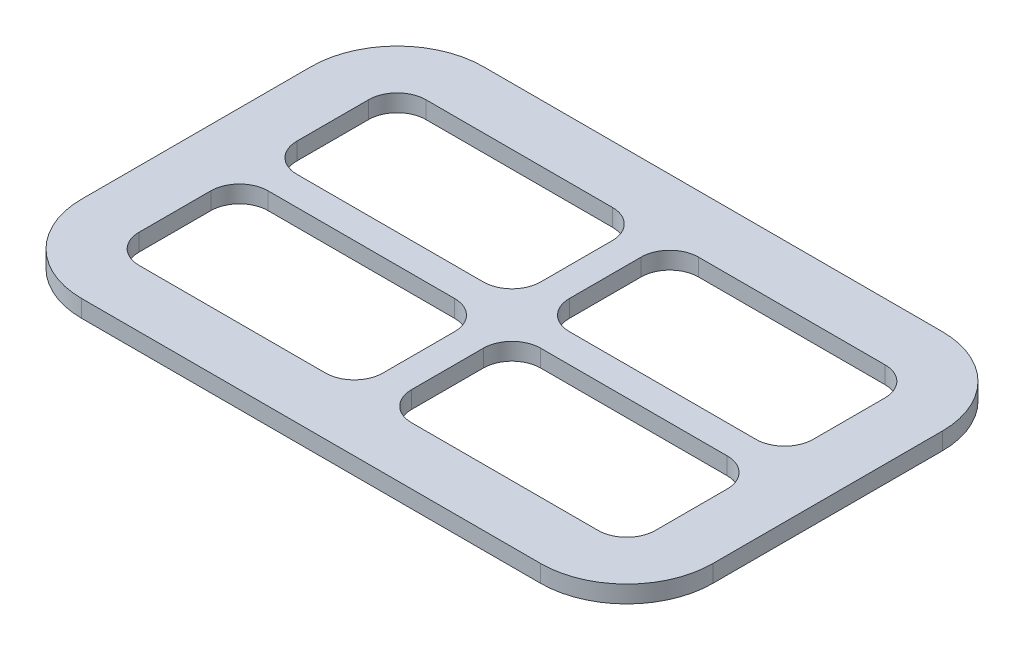
SolidWorks part; units mm, degrees
ref_plane "Plano frontal" through (0, 0, 0) normal (0, 0, 1) x (1, 0, 0)
ref_plane "Plano superior" through (0, 0, 0) normal (0, 1, 0) x (1, 0, 0)
ref_plane "Plano direito" through (0, 0, 0) normal (1, 0, 0) x (0, 0, -1)
sketch "Esboço1" plane through (0, 0, 0) normal (0, 1, 0) x (1, 0, 0)
  line L1 (110, -70) -> (-110, -70)
  line L2 (110, -70) -> (110, 70)
  line L3 (110, 70) -> (-110, 70)
  line L4 (-110, -70) -> (-110, 70)
  line L5 (110, -70) -> (-110, 70) construction
  line L6 (110, 70) -> (-110, -70) construction
  point P0 (0, 0)
  dimension "D1" = 220
  dimension "D2" = 140
extrude "Ressalto-extrusão1" add sketch "Esboço1" along normal blind 6
sketch "Esboço2" plane through (0, 6, 0) normal (0, 1, 0) x (1, 0, 0)
  line L4 (90, 5) -> (90, 50)
  line L6 (-5, 50) -> (-5, 5)
  line L7 (90, 5) -> (5, 5)
  line L8 (-90, 50) -> (-90, -50)
  line L9 (-90, -50) -> (90, -50)
  line L10 (90, -50) -> (90, 50)
  line L11 (90, 50) -> (-90, 50)
  line L12 (-90, 50) -> (-90, 5)
  line L13 (-90, -50) -> (-5, -50)
  line L14 (90, -50) -> (90, -5)
  line L15 (90, 50) -> (5, 50)
  line L16 (5, 50) -> (5, 5)
  line L17 (90, -5) -> (5, -5)
  line L18 (-90, -5) -> (-90, -50)
  line L20 (-5, -5) -> (-5, -50)
  line L24 (5, -5) -> (5, -50)
  line L26 (-5, -5) -> (-90, -5)
  line L28 (-5, 5) -> (-90, 5)
  line L30 (-5, 50) -> (-90, 50)
  line L31 (5, -50) -> (90, -50)
  dimension "D1" = 20
extrude "Corte-extrusão1" cut sketch "Esboço2" against normal blind 6
fillet "Filete1" radius 30 4 edges at (110, 3, 70) (-110, 3, 70) (-110, 3, -70) (110, 3, -70)
fillet "Filete2" radius 10 16 edges at (90, 3, -5) (-5, 3, -5) (-5, 3, 50) (90, 3, 50) (90, 3, 5) (-5, 3, 5) (90, 3, -50) (-5, 3, -50) (5, 3, 5) (5, 3, -50) (-90, 3, -50) (-90, 3, 5) (5, 3, 50) (5, 3, -5) (-90, 3, -5) (-90, 3, 50)
